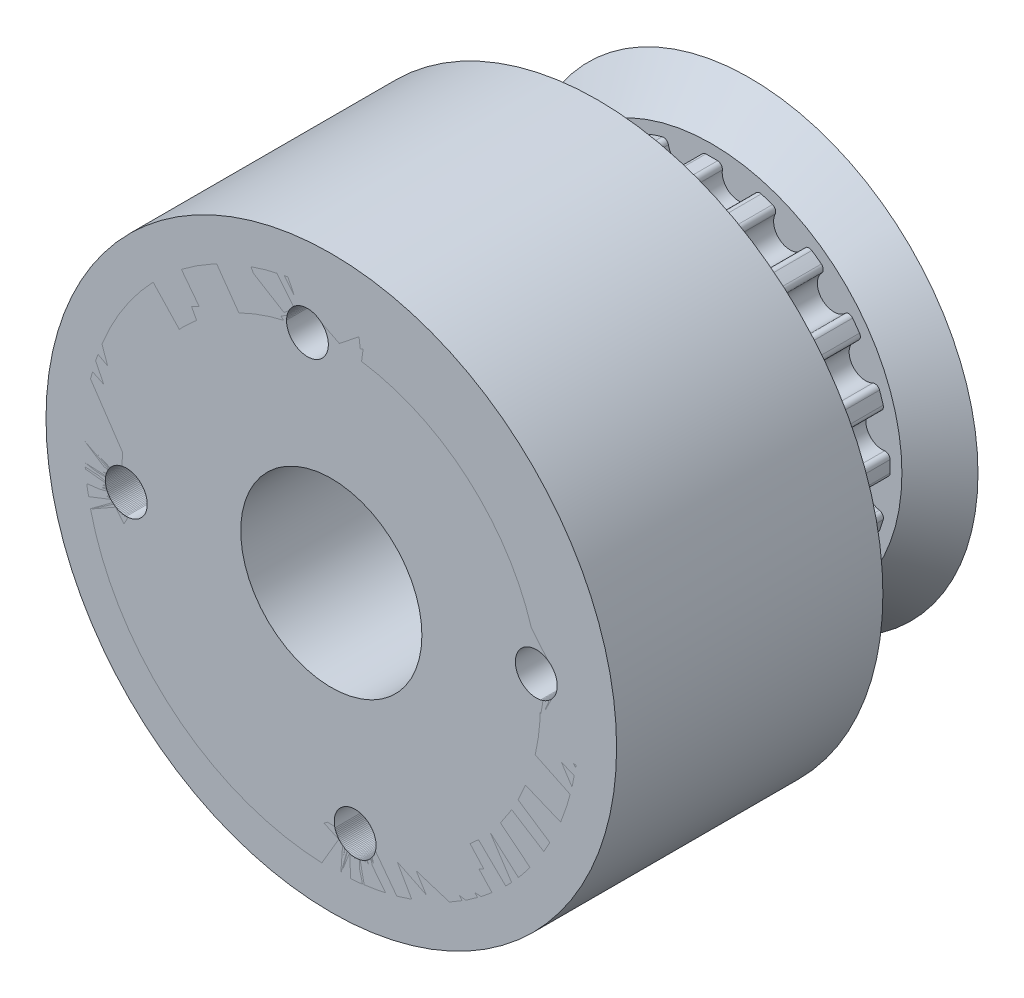
SolidWorks part; units mm, degrees
ref_plane "Front Plane" through (0, 0, 0) normal (0, 0, 1) x (1, 0, 0)
ref_plane "Top Plane" through (0, 0, 0) normal (0, 1, 0) x (1, 0, 0)
ref_plane "Right Plane" through (0, 0, 0) normal (1, 0, 0) x (0, 0, -1)
ref_plane "back of wheel" through (0, 0, 0) normal (0, 0, 1) x (1, 0, 0)
ref_plane "front of wheel" through (0, 0, 14) normal (0, 0, 1) x (1, 0, 0)
sketch "sketch for modifier" plane through (0, 0, 0) normal (0, 0, 1) x (1, 0, 0)
  circle A0 centre (0, 0) radius 11
  circle A2 centre (0, 0) radius 15
  dimension "D1" = 30
  dimension "D2" = 4
sketch "wheel outline" plane through (0, 0, 0) normal (0, 0, 1) x (1, 0, 0)
  circle A0 centre (0, 0) radius 13
  circle A1 centre (0, 0) radius 4.7625
  circle A2 centre (0, 0) radius 15 construction
  point P6 (0, 4.7625)
  dimension "D1" = 9.525
  dimension "D2" = 2
sketch "sketch for clamp hub" plane through (0, 0, 0) normal (0, 0, 1) x (1, 0, 0)
  line L0 (-11.3137, 0) -> (0, 11.3137)
  line L1 (0, 11.3137) -> (11.3137, 0)
  line L2 (11.3137, 0) -> (0, -11.3137)
  line L3 (0, -11.3137) -> (-11.3137, 0)
  dimension "D1" = 16
sketch "whole locations" plane through (0, 0, 0) normal (0, 0, 1) x (1, 0, 0)
  line L0 (6.35, 0) -> (-6.35, 0) construction
  point P4 (0, 0)
  point P5 (6.35, 0)
  point P6 (-6.35, 0)
  dimension "D1" = 12.7
sketch "pilly outside" plane through (0, 0, 0) normal (0, 0, 1) x (1, 0, 0)
  line L0 (6.35, 0) -> (-6.35, 0) construction
  circle A0 centre (0, 0) radius 10
  dimension "D1" = 20
sketch "sketch for tooth geometry" plane through (0, 0, 0) normal (0, 0, 1) x (1, 0, 0)
  line L0 (0, 0) -> (0, 10) construction
  line L1 (0, 0) -> (1.5643, 9.8769) construction
  line L2 (0, 10) -> (0, 9.385)
  line L3 (2.9001, 8.9257) -> (3.0902, 9.5106)
  circle A0 centre (0, 0) radius 10 construction
  arc A1 (0.3094, 9.3799) -> (0.5586, 9.0862) centre (0.3008, 9.12) cw
  arc A2 (0.5586, 9.0862) -> (2.2766, 8.8141) centre (1.4212, 8.9731) ccw
  arc A3 (2.2766, 8.8141) -> (2.6043, 9.0164) centre (2.5322, 8.7666) cw
  arc A6 (0, 10) -> (3.0902, 9.5106) centre (0, 0) cw
  arc A7 (0, 9.385) -> (0.3094, 9.3799) centre (0, 0) cw
  arc A8 (2.6043, 9.0164) -> (2.9001, 8.9257) centre (0, 0) cw
  point P12 (1.2851, 8.1139)
  dimension "D1" = 0.26
  dimension "D3" = 0.87
  dimension "D4" = 1.785
  dimension "tooth angle" = 9
  dimension "D2" = 0.615
ref_plane "back of toothed part" through (0, 0, -6) normal (0, 0, 1) x (1, 0, 0)
ref_plane "plane for revolve" through (0, 0, 0) normal (1, 0, 0) x (0, 0, -1)
sketch "pully holder sketch" plane through (0, 0, 0) normal (1, 0, 0) x (0, 0, -1)
  line L0 (6, 10) -> (8, 12)
  line L2 (8, 12) -> (8, 4.7625)
  line L3 (8, 4.7625) -> (6, 4.7625)
  line L4 (6, 4.7625) -> (6, 10)
  line L5 (6, 27.5) -> (6, -27.5) construction
  line L7 (6, 0) -> (8, 0) construction
  dimension "D1" = 2
  dimension "D2" = 2
ref_plane "inside plane" through (0, 0, -8) normal (0, 0, 1) x (1, 0, 0)
ref_plane "end of hub whole" through (0, 0, -2) normal (0, 0, 1) x (1, 0, 0)
sketch "Sketch3" plane through (0, 0, 0) normal (0, 0, 1) x (1, 0, 0)
  circle A1 centre (0, 0) radius 13
  circle A2 centre (0, 0) radius 13
  circle A3 centre (0, 0) radius 4.7625
  circle A4 centre (0, 0) radius 4.7625
  dimension "D1" = 0
  dimension "D2" = 0
extrude "wheel body" add sketch "Sketch3" along normal up to surface (14 mm away) up to plane "front of wheel"
sketch "Sketch13" plane through (0, 0, 0) normal (0, 0, 1) x (1, 0, 0)
  circle A0 centre (0, 0) radius 10 construction
  circle A1 centre (0, 0) radius 10
  circle A2 centre (0, 0) radius 4.7625 construction
  circle A3 centre (0, 0) radius 4.7625
extrude "pully" add sketch "Sketch13" against normal up to surface (6 mm away) up to plane "back of toothed part"
sketch "Sketch9" plane through (0, 0, 0) normal (0, 0, 1) x (1, 0, 0)
  circle A1 centre (0, 0) radius 15
  circle A2 centre (0, 0) radius 15
  circle A3 centre (0, 0) radius 11
  circle A4 centre (0, 0) radius 11
  dimension "D1" = 0
  dimension "D2" = 0
extrude "modifer" add sketch "Sketch9" along normal up to surface (14 mm away) separate body up to plane "front of wheel"
sketch "Sketch16" plane through (0, 0, 0) normal (1, 0, 0) x (0, 0, -1)
  line L4 (8, 12) -> (6, 10)
  line L5 (8, 4.7625) -> (8, 12)
  line L6 (6, 4.7625) -> (8, 4.7625)
  line L7 (6, 10) -> (6, 4.7625)
  line L8 (8, 12) -> (6, 10)
  line L9 (8, 4.7625) -> (8, 12)
  line L10 (6, 4.7625) -> (8, 4.7625)
  line L11 (6, 10) -> (6, 4.7625)
  dimension "D1" = 0
revolve "pulley holder" add sketch "Sketch16" angle 360 about L7
sketch "Sketch6" plane through (0, 0, -8) normal (0, 0, 1) x (1, 0, 0)
  line L4 (0, 11.3137) -> (-11.3137, 0)
  line L5 (11.3137, 0) -> (0, 11.3137)
  line L6 (0, -11.3137) -> (11.3137, 0)
  line L7 (-11.3137, 0) -> (0, -11.3137)
  line L8 (0, 11.3137) -> (-11.3137, 0)
  line L9 (11.3137, 0) -> (0, 11.3137)
  line L10 (0, -11.3137) -> (11.3137, 0)
  line L11 (-11.3137, 0) -> (0, -11.3137)
  dimension "D1" = 0
sketch "Sketch17" plane through (0, 0, 0) normal (0, 0, 1) x (1, 0, 0)
  line L6 (2.9001, 8.9257) -> (3.0902, 9.5106)
  line L7 (0, 10) -> (0, 9.385)
  line L10 (2.9001, 8.9257) -> (3.0902, 9.5106)
  line L11 (0, 10) -> (0, 9.385)
  arc A18 (2.9001, 8.9257) -> (2.6043, 9.0164) centre (0, 0) ccw
  arc A19 (2.6043, 9.0164) -> (2.2766, 8.8141) centre (2.5322, 8.7666) ccw
  arc A20 (0.5586, 9.0862) -> (2.2766, 8.8141) centre (1.4212, 8.9731) ccw
  arc A21 (0.5586, 9.0862) -> (0.3094, 9.3799) centre (0.3008, 9.12) ccw
  arc A22 (0.3094, 9.3799) -> (0, 9.385) centre (0, 0) ccw
  arc A23 (3.0902, 9.5106) -> (0, 10) centre (0, 0) ccw
  arc A30 (2.9001, 8.9257) -> (2.6043, 9.0164) centre (0, 0) ccw
  arc A31 (2.6043, 9.0164) -> (2.2766, 8.8141) centre (2.5322, 8.7666) ccw
  arc A32 (0.5586, 9.0862) -> (2.2766, 8.8141) centre (1.4212, 8.9731) ccw
  arc A33 (0.5586, 9.0862) -> (0.3094, 9.3799) centre (0.3008, 9.12) ccw
  arc A34 (0.3094, 9.3799) -> (0, 9.385) centre (0, 0) ccw
  arc A35 (3.0902, 9.5106) -> (0, 10) centre (0, 0) ccw
  dimension "D1" = 0
extrude "tooth geometetry" cut sketch "Sketch17" against normal up to surface (6 mm away) up to plane "back of toothed part"
pattern_circular "tooth pattern" count 20 over 360 about axis through (0, 0, 0) along (0, 0, 1) of "tooth geometetry"
hole_wizard "M2 Clearance Hole1" positions "Sketch18" profile "Sketch19" hole size "M2" standard "ANSI Metric"
sketch "Sketch18" plane through (0, 0, 14) normal (0, 0, 1) x (1, 0, 0)
  point P0 (-1.255, 10.7772)
  point P3 (-10.7772, -1.255)
  point P6 (10.7772, 1.255)
  point P8 (1.255, -10.7772)
  point P12 (8.4252, 0)
  point P16 (0, 0)
  point P17 (11.0255, 1.2839)
sketch "Sketch19" plane through (-1.255, 10.7772, 14) normal (1, 0, 0) x (0, -1, 0)
  line L0 (0, 0) -> (0, 8.1609)
  line L1 (0, 8.1609) -> (1.1, 7.5)
  line L2 (1.1, 7.5) -> (1.1, 0)
  line L5 (1.1, 0) -> (0, 0)
  line L10 (0, 8.1609) -> (-1.1, 7.5) construction
  line L11 (0, -6.35) -> (0, 107.95) construction
  dimension "Hole Dia." = 2.2
  dimension "Hole Depth" = 7.5
  dimension "Drill Angle" = 118
equation "\"number of teeth\"= 20"
equation "\"tooth angle@sketch for tooth geometry\"= ( 360 / \"number of teeth\" ) / 2"
equation "\"number of teeth@tooth pattern\"= \"number of teeth\""
